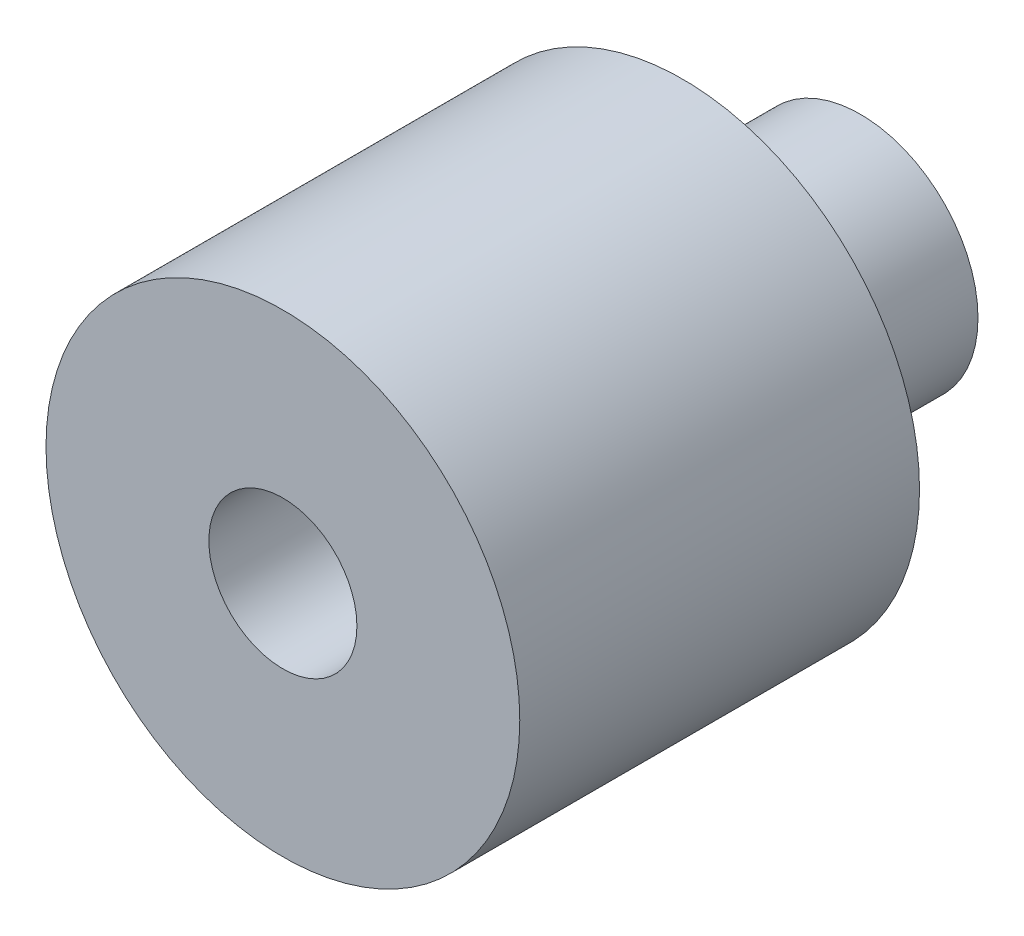
SolidWorks part; units mm, degrees
ref_plane "Front Plane" through (0, 0, 0) normal (0, 0, 1) x (1, 0, 0)
ref_plane "Top Plane" through (0, 0, 0) normal (0, 1, 0) x (1, 0, 0)
ref_plane "Right Plane" through (0, 0, 0) normal (1, 0, 0) x (0, 0, -1)
sketch "Sketch1" plane through (0, 0, 0) normal (0, 0, 1) x (1, 0, 0)
  circle A0 centre (0, 0) radius 8
  dimension "D1" = 16
extrude "Boss-Extrude1" add sketch "Sketch1" along normal blind 13.5
sketch "Sketch3" plane through (0, 0, 0) normal (0, 0, -1) x (-1, 0, 0)
  circle A0 centre (0, 0) radius 3.975
  dimension "D1" = 7.95
extrude "Boss-Extrude2" add sketch "Sketch3" along normal blind 6
sketch "Sketch4" plane through (0, 0, 13.5) normal (0, 0, 1) x (1, 0, 0)
  circle A0 centre (0, 0) radius 2.5
  dimension "D1" = 5
extrude "Cut-Extrude2" cut sketch "Sketch4" against normal blind 13
sketch "Sketch7" plane through (0, 0, -6) normal (0, 0, -1) x (-1, 0, 0)
  circle A0 centre (0, 0) radius 2
  dimension "D1" = 4
extrude "Cut-Extrude3" cut sketch "Sketch7" against normal blind 5
